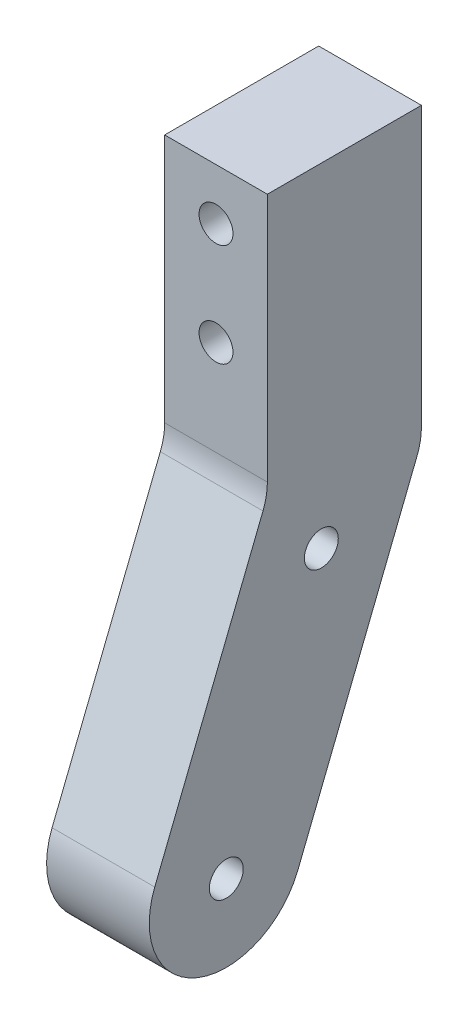
SolidWorks part; units mm, degrees
material "1060 合金"
ref_plane "正面" through (0, 0, 0) normal (0, 0, 1) x (1, 0, 0)
ref_plane "平面" through (0, 0, 0) normal (0, 1, 0) x (1, 0, 0)
ref_plane "右側面" through (0, 0, 0) normal (1, 0, 0) x (0, 0, -1)
sketch "ｽｹｯﾁ1" plane through (0, 0, 0) normal (1, 0, 0) x (0, 0, -1)
  line L0 (0, 0) -> (-9.2558, -23.2235) construction
  line L1 (0, 0) -> (0, 38.7799) construction
  line L2 (0, 0) -> (-22.2474, -11.4042) construction
  line L3 (-32.2474, -32.5) -> (32.2474, -32.5)
  line L4 (-32.2474, -32.5) -> (-32.2474, 32.5)
  line L5 (-32.2474, 32.5) -> (32.2474, 32.5)
  line L6 (32.2474, -32.5) -> (32.2474, 32.5)
  line L7 (-32.2474, -32.5) -> (32.2474, 32.5) construction
  line L8 (-32.2474, 32.5) -> (32.2474, -32.5) construction
  circle A0 centre (0, 0) radius 1.65
  circle A1 centre (-9.2558, -23.2235) radius 1.65
  circle A2 centre (-22.2474, -11.4042) radius 1.65
  dimension "D2" = 3.3
  dimension "D4" = 65
  dimension "D5" = 10
  dimension "D1" = 21.73
  dimension "D3" = 25
  dimension "D6" = 41.13
  dimension "D7" = 25
extrude "ﾎﾞｽ - 押し出し1" add sketch "ｽｹｯﾁ1" along normal blind 10
sketch "ｽｹｯﾁ2" plane through (10, 0, 0) normal (1, 0, 0) x (0, 0, -1)
  line L0 (0, 0) -> (-9.2558, -23.2235) construction
  line L1 (-20.4379, -31.0226) -> (-4.1903, 9.7438) construction
  line L2 (-20.4379, -31.0226) -> (-6.5039, -36.5761) construction
  line L3 (-4.1903, 9.7438) -> (9.7438, 4.1903) construction
  line L4 (-6.5039, -36.5761) -> (9.7438, 4.1903) construction
  line L5 (-20.4379, -31.0226) -> (9.7438, 4.1903) construction
  line L6 (-4.1903, 9.7438) -> (-6.5039, -36.5761) construction
  line L7 (9.7438, 4.1903) -> (9.7438, 32.5)
  line L8 (32.2474, 32.5) -> (-32.2474, 32.5) construction
  line L9 (-2.2888, -26.0002) -> (9.7438, 4.1903)
  line L10 (19.7438, 12.5) -> (9.7438, 12.5) construction
  line L11 (19.7438, 12.5) -> (19.7438, 32.5) construction
  line L12 (19.7438, 32.5) -> (9.7438, 32.5) construction
  line L13 (9.7438, 12.5) -> (9.7438, 32.5) construction
  line L14 (19.7438, 12.5) -> (9.7438, 32.5) construction
  line L15 (19.7438, 32.5) -> (9.7438, 12.5) construction
  line L16 (9.7438, 32.5) -> (-5.2562, 32.5)
  line L17 (-16.2229, -20.4467) -> (-5.2562, 7.0693)
  line L18 (-5.2562, 7.0693) -> (-5.2562, 32.5)
  line L19 (-14.3029, -28.7711) -> (-27.2945, -16.9518)
  line L20 (-32.2474, -32.5) -> (32.2474, -32.5)
  line L21 (-32.2474, -32.5) -> (-32.2474, 32.5)
  line L22 (-32.2474, 32.5) -> (32.2474, 32.5)
  line L23 (32.2474, -32.5) -> (32.2474, 32.5)
  line L24 (-32.2474, -32.5) -> (32.2474, 32.5) construction
  line L25 (-32.2474, 32.5) -> (32.2474, -32.5) construction
  line L26 (-5.2562, 7.0693) -> (-25.9982, -4.9094)
  circle A0 centre (-9.2558, -23.2235) radius 7.5
  circle A1 centre (0, 0) radius 7.5
  circle A2 centre (-22.2474, -11.4042) radius 7.5
  point P6 (14.7438, 22.5)
  point P7 (-5.3471, -13.4162)
  point P33 (-9.1463, -36.0063)
  line M5 (32.2474, -32.5) -> (32.2474, 32.5)
  line M6 (32.2474, 32.5) -> (-32.2474, 32.5)
  line M7 (-32.2474, 32.5) -> (-32.2474, -32.5)
  line M8 (-32.2474, -32.5) -> (32.2474, -32.5)
  circle M34 centre (-22.2474, -11.4042) radius 1.65
  dimension "D1" = 15
  dimension "D2" = 7.5
  dimension "D3" = 15
  dimension "D4" = 10
  dimension "D5" = 20
  dimension "D6" = 15
extrude "ｶｯﾄ - 押し出し1" cut sketch "ｽｹｯﾁ2" against normal through all contours A0 L17 L18 L7 L9 M6 M7 M8 M5 | A2 L19 A0 L17 L26 | A2 M34
sketch "ｽｹｯﾁ3" plane through (0, 0, -9.7438) normal (0, 0, -1) x (-1, 0, 0)
  line L0 (-5, 32.5) -> (-5, 4.1903) construction
  line L1 (0, 32.5) -> (-10, 32.5) construction
  line L2 (0, 4.1903) -> (-10, 4.1903) construction
  circle A0 centre (-5, 27.5) radius 1.65
  circle A1 centre (-5, 17.5) radius 1.65
  dimension "D1" = 5
  dimension "D2" = 10
  dimension "D3" = 3.3
extrude "ｶｯﾄ - 押し出し2" cut sketch "ｽｹｯﾁ3" against normal through all
fillet "ﾌｨﾚｯﾄ1" radius 6 2 edges at (5, 4.1903, -9.7438) (5, 7.0693, 5.2562)
